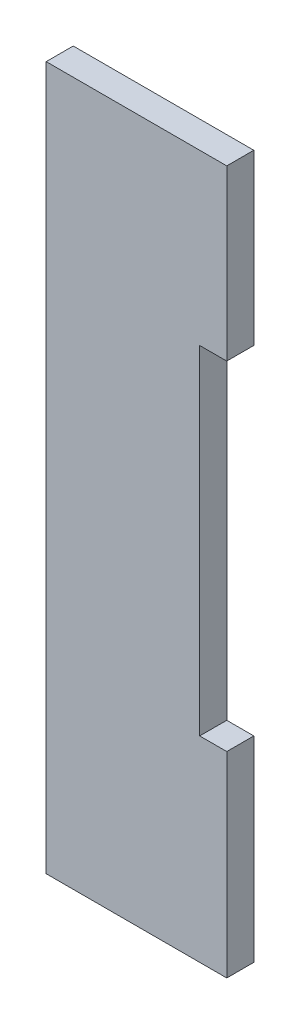
SolidWorks part; units mm, degrees
ref_plane "Спереди" through (0, 0, 0) normal (0, 0, 1) x (1, 0, 0)
ref_plane "Сверху" through (0, 0, 0) normal (0, 1, 0) x (1, 0, 0)
ref_plane "Справа" through (0, 0, 0) normal (1, 0, 0) x (0, 0, -1)
sketch "Эскиз1" plane through (0, 0, 0) normal (0, 0, 1) x (1, 0, 0)
  line L2 (3, -25.5828) -> (3, 24.4172)
  line L4 (-19.7, -50.5828) -> (-19.7, -0.5828)
  line L5 (-19.7, -50.5828) -> (-19.7, -54.5828)
  line L6 (3, 24.4172) -> (7, 24.4172)
  line L7 (7, 49.4172) -> (7, 24.4172)
  line L9 (-19.7, -54.5828) -> (7, -54.5828)
  line L10 (3, -25.5828) -> (7, -25.5828)
  line L11 (7, -50.5828) -> (7, -25.5828)
  line L12 (-19.7, 49.4172) -> (7, 49.4172)
  line L13 (7, -50.5828) -> (7, -54.5828)
  line L16 (-19.7, -0.5828) -> (-19.7, 49.4172)
  point P10 (-19.7, -0.5828)
  dimension "D1" = 4
  dimension "D2" = 25
  dimension "D3" = 25
  dimension "D4" = 4
  dimension "D5" = 100
  dimension "D6" = 22.7
extrude "Бобышка-Вытянуть1" add sketch "Эскиз1" along normal blind 4
